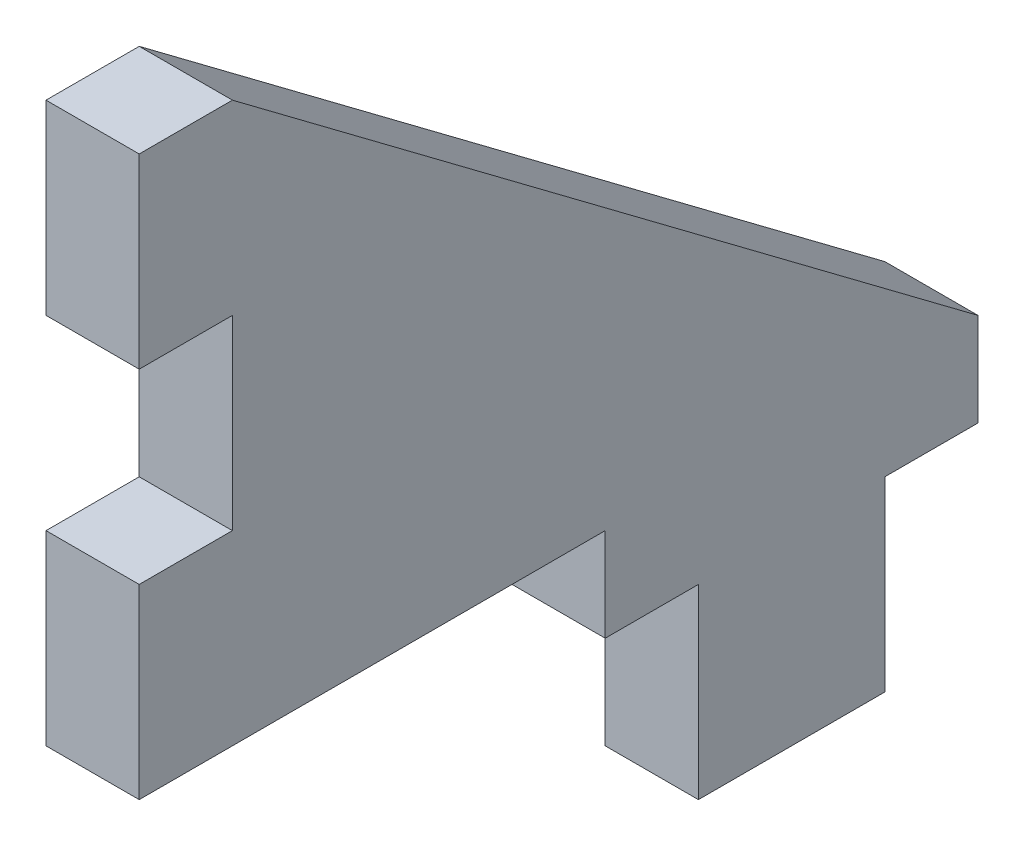
SolidWorks part; units mm, degrees
material "Maple"
ref_plane "Front" through (0, 0, 0) normal (0, 0, 1) x (1, 0, 0)
ref_plane "Top" through (0, 0, 0) normal (0, 1, 0) x (1, 0, 0)
ref_plane "Right" through (0, 0, 0) normal (1, 0, 0) x (0, 0, -1)
sketch "Sketch2" plane through (0, 0, 0) normal (1, 0, 0) x (0, 0, -1)
  line L0 (-8.75, 11.25) -> (-8.75, -11.25) construction
  line L1 (-11.25, -11.25) -> (11.25, -11.25) construction
  line L2 (-11.25, -11.25) -> (-11.25, 11.25) construction
  line L3 (-11.25, 11.25) -> (11.25, 11.25) construction
  line L4 (11.25, -11.25) -> (11.25, 11.25) construction
  line L5 (-11.25, -11.25) -> (11.25, 11.25) construction
  line L6 (-11.25, 11.25) -> (11.25, -11.25) construction
  line L7 (-11.25, -3.75) -> (11.25, -3.75) construction
  line L8 (-8.75, 11.25) -> (11.25, -3.75)
  line L11 (3.75, -11.25) -> (3.75, -6.25)
  line L13 (-11.25, -3.75) -> (-11.25, 1.25)
  line L14 (-11.25, 1.25) -> (-8.75, 1.25)
  line L15 (-8.75, 1.25) -> (-8.75, 6.25)
  line L16 (-8.75, 6.25) -> (-11.25, 6.25)
  line L17 (-11.25, 6.25) -> (-11.25, 11.25)
  line L18 (-11.25, 11.25) -> (-8.75, 11.25)
  line L19 (-11.25, -3.75) -> (1.25, -3.75)
  line L20 (1.25, -3.75) -> (1.25, -6.25)
  line L21 (1.25, -6.25) -> (3.75, -6.25)
  line L22 (11.25, -3.75) -> (11.25, -6.25)
  line L23 (11.25, -6.25) -> (8.75, -6.25)
  line L24 (8.75, -6.25) -> (8.75, -11.25)
  line L25 (8.75, -11.25) -> (3.75, -11.25)
  point P0 (0, 0)
  point P19 (-40.8029, 6.1018)
  point P21 (-0.1373, -3.75)
  dimension "D1" = 22.5
  dimension "D2" = 22.5
  dimension "D3" = 2.5
  dimension "D4" = 7.5
  dimension "D6" = 2.5
extrude "Boss-Extrude1" add sketch "Sketch2" along normal blind 2.5 contours L8 L22 L23 L24 L25 L11 L21 L20 L19 L13 L14 L15 L16 L17 L18
